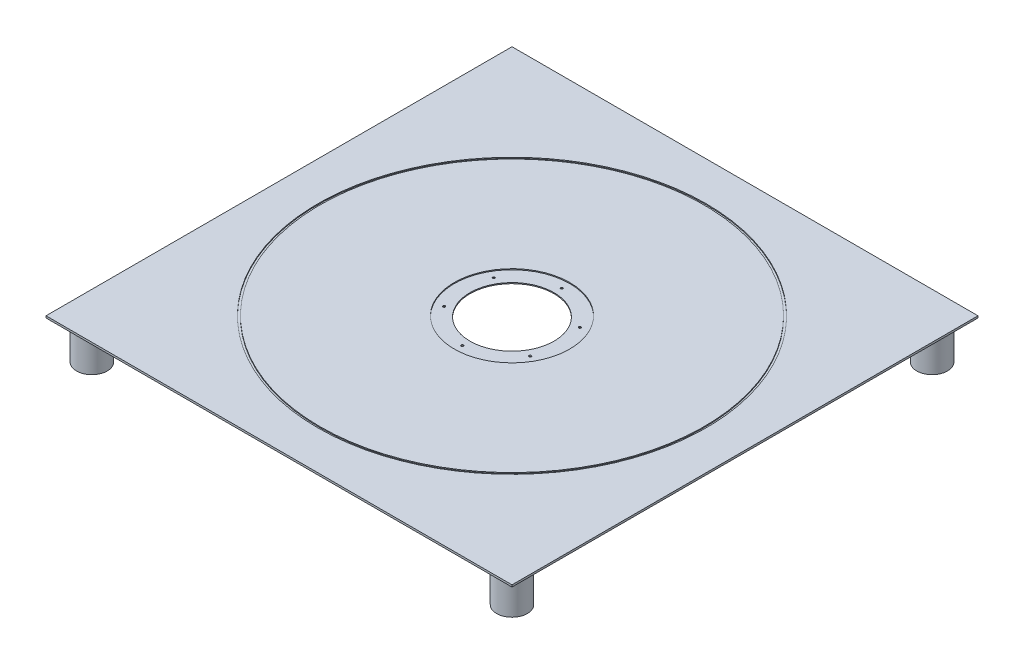
SolidWorks part; units mm, degrees
ref_plane "Front Plane" through (0, 0, 0) normal (0, 0, 1) x (1, 0, 0)
ref_plane "Top Plane" through (0, 0, 0) normal (0, 1, 0) x (1, 0, 0)
ref_plane "Right Plane" through (0, 0, 0) normal (1, 0, 0) x (0, 0, -1)
sketch "Sketch2" plane through (0, 0, 0) normal (0, 1, 0) x (1, 0, 0)
  line L1 (-304.8, -304.8) -> (304.8, -304.8)
  line L2 (-304.8, -304.8) -> (-304.8, 304.8)
  line L3 (-304.8, 304.8) -> (304.8, 304.8)
  line L4 (304.8, -304.8) -> (304.8, 304.8)
  line L5 (-304.8, -304.8) -> (304.8, 304.8) construction
  line L6 (-304.8, 304.8) -> (304.8, -304.8) construction
  point P0 (0, 0)
  dimension "D1" = 609.6
  dimension "D2" = 609.6
extrude "Boss-Extrude1" add sketch "Sketch2" along normal blind 2.54
sketch "Sketch5" plane through (0, 2.54, 0) normal (0, 1, 0) x (1, 0, 0)
  circle A0 centre (0, 0) radius 75.5
  dimension "D1" = 151
extrude "Cut-Extrude1" cut sketch "Sketch5" against normal blind 1.27 and the other way through all
sketch "Sketch7" plane through (0, 1.27, 0) normal (0, 1, 0) x (1, 0, 0)
  circle A0 centre (0, 0) radius 55
  dimension "D1" = 110
extrude "Cut-Extrude2" cut sketch "Sketch7" against normal through all both and the other way through all contours A0
sketch "Sketch12" plane through (0, 0, 0) normal (0, -1, 0) x (1, 0, 0)
  line L0 (-304.8, 304.8) -> (304.8, 304.8) construction
  line L1 (-304.8, -304.8) -> (-304.8, 304.8) construction
  circle A0 centre (-274.8, 274.8) radius 20.1233
  dimension "D1" = 30
  dimension "D2" = 30
extrude "Boss-Extrude2" add sketch "Sketch12" along normal blind 50 contours A0
sketch "Sketch13" plane through (0, 1.27, 0) normal (0, 1, 0) x (1, 0, 0)
  circle A3 centre (0, 65) radius 1.5
  dimension "D2" = 3
extrude "Cut-Extrude3" cut sketch "Sketch13" against normal blind 10
pattern_circular "CirPattern2" count 6 over 360 about axis through (0, 0, 0) along (0, 1, 0) of "Cut-Extrude3"
ref_plane "Plane1" through (0, 0, 0) normal (1, 0, 0) x (0, 0, -1)
ref_plane "Plane2" through (0, 0, 0) normal (0, 0, 1) x (1, 0, 0)
mirror "Mirror1" about plane through (0, 0, 0) normal (0, 0, 1) of "Boss-Extrude2" second plane through (0, 0, 0) second plane normal (1, 0, 0)
ref_plane "Plane3" through (0, 2.54, 0) normal (0, 1, 0) x (1, 0, 0)
sketch "Sketch15" plane through (0, 2.54, 0) normal (0, 1, 0) x (1, 0, 0)
  circle A1 centre (0, 203.2) radius 1.524
  circle A2 centre (175.9764, 101.6) radius 1.524
  circle A3 centre (175.9764, -101.6) radius 1.524
  circle A4 centre (0, -203.2) radius 1.524
  circle A5 centre (-175.9764, -101.6) radius 1.524
  circle A6 centre (-175.9764, 101.6) radius 1.524
  point P18 (0, 0)
  dimension "D1" = 6
  dimension "D2" = 3.048
  dimension "D3" = 203.2
extrude "Cut-Extrude4" [suppressed] cut sketch "Sketch15" against normal blind 10 contours A1
sketch "Sketch16" plane through (0, 2.54, 0) normal (0, 1, 0) x (1, 0, 0)
  circle A0 centre (0, 0) radius 254
  circle A2 centre (0, 0) radius 251.206
  dimension "D1" = 508
  dimension "D2" = 2.794
extrude "Cut-Extrude6" cut sketch "Sketch16" against normal blind 1.27 contours A2 | A0
